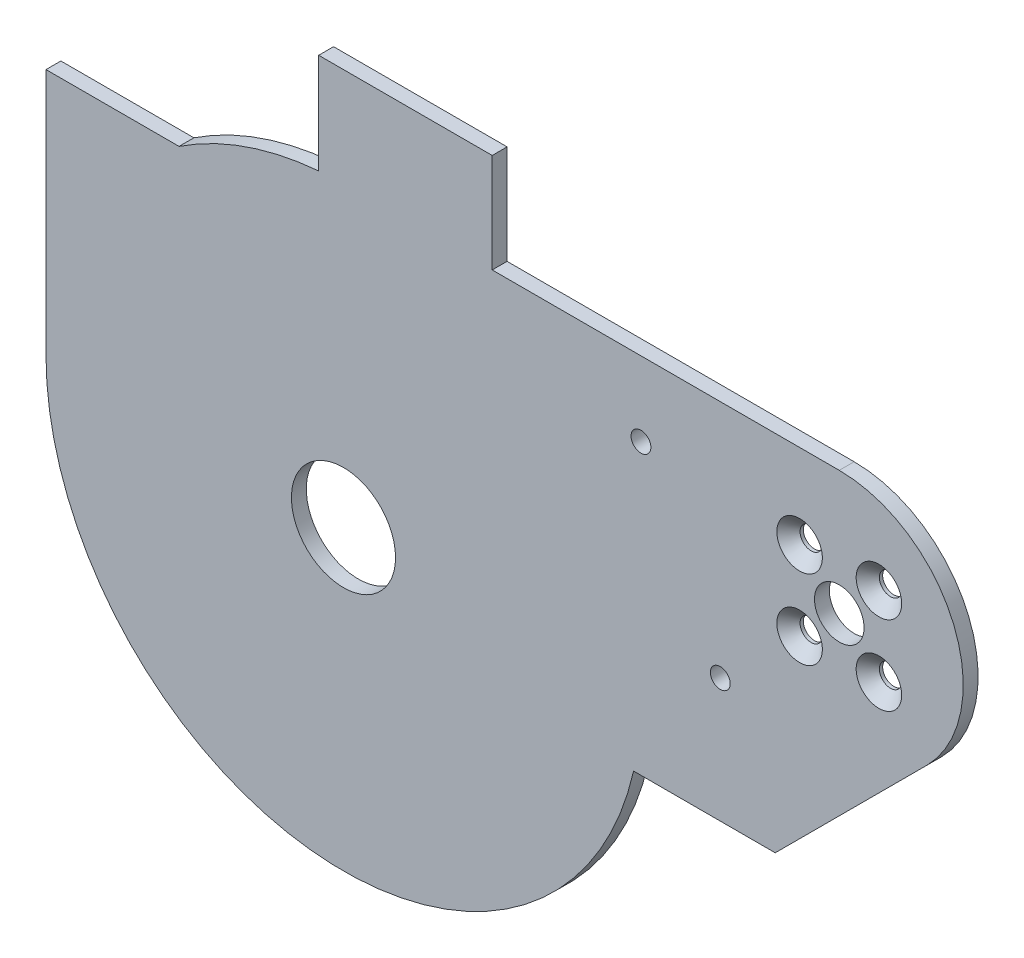
SolidWorks part; units mm, degrees
ref_plane "前视基准面" through (0, 0, 0) normal (0, 0, 1) x (1, 0, 0)
ref_plane "上视基准面" through (0, 0, 0) normal (0, 1, 0) x (1, 0, 0)
ref_plane "右视基准面" through (0, 0, 0) normal (1, 0, 0) x (0, 0, -1)
sketch "Sketch1" plane through (0, 0, 0) normal (0, 0, 1) x (1, 0, 0)
  line L0 (-10.9179, 60) -> (113.3582, 60) construction
  line L3 (-33.1662, 50) -> (-60, 50)
  line L4 (-60, 0) -> (-60, 50)
  line L6 (67.51, -32.8453) -> (81.2655, -19.0899) construction
  line L7 (81.2655, -19.0899) -> (117.6777, 17.3223)
  line L12 (58.5132, -13.2742) -> (87.0811, -13.2742)
  line L13 (0, 60) -> (100, 60)
  arc A0 (0, 60) -> (58.5132, -13.2742) centre (0, 0) ccw
  circle A2 centre (0, 0) radius 10.5
  arc A8 (117.6777, 17.3223) -> (100, 60) centre (100, 35) ccw
  circle A9 centre (100, 35) radius 5
  dimension "D1" = 120
  dimension "D3" = 21
  dimension "D5" = 50
  dimension "D4" = 100
  dimension "D6" = 10
extrude "Boss-Extrude1" add sketch "Sketch1" along normal blind 3
sketch "Sketch2" plane through (0, 0, 3) normal (0, 0, 1) x (1, 0, 0)
  line L1 (-60, 0) -> (-60, 50) construction
  line L2 (0, 60) -> (100, 60) construction
  line L3 (58.5132, -13.2742) -> (87.0811, -13.2742) construction
  circle A1 centre (0, 0) radius 57
  circle A2 centre (60, 45) radius 2
  circle A3 centre (76, 11.7258) radius 2
  circle A6 centre (100, 35) radius 14
  dimension "D1" = 15
  dimension "D4" = 136
  dimension "D5" = 28
  dimension "D2" = 120
  dimension "D3" = 25
extrude "Cut-Extrude1" cut sketch "Sketch2" against normal up to next contours A2 | A3
sketch "Sketch3" plane through (0, 0, 0) normal (0, 0, -1) x (-1, 0, 0)
  line L4 (-30, 0) -> (-30, 80)
  line L5 (-30, 80) -> (5, 80)
  line L6 (5, 80) -> (5, 48)
  line L7 (5, 48) -> (25.3049, 16.1141)
  circle A2 centre (0, 0) radius 10.5
  arc A4 (-30, 0) -> (25.3049, 16.1141) centre (0, 0) ccw
  dimension "D1" = 80
  dimension "D2" = 35
  dimension "D3" = 32
extrude "Boss-Extrude2" add sketch "Sketch3" against normal blind 3
sketch "Sketch4" plane through (0, 0, 0) normal (0, 0, -1) x (-1, 0, 0)
  line L0 (-30, 80) -> (5, 80) construction
  line L1 (5, 80) -> (5, 48) construction
  line L3 (-20, 65.5961) -> (-5, 65.5961)
  line L4 (-20, 65.5961) -> (-20, 63.5961)
  line L5 (-20, 63.5961) -> (-5, 63.5961)
  line L6 (-5, 65.5961) -> (-5, 63.5961)
  line L7 (-20, 65.5961) -> (-5, 63.5961) construction
  line L8 (-20, 63.5961) -> (-5, 65.5961) construction
  line L9 (-13.5, 72.0961) -> (-11.5, 72.0961)
  line L10 (-13.5, 72.0961) -> (-13.5, 57.0961)
  line L11 (-13.5, 57.0961) -> (-11.5, 57.0961)
  line L12 (-11.5, 72.0961) -> (-11.5, 57.0961)
  line L13 (-13.5, 72.0961) -> (-11.5, 57.0961) construction
  line L14 (-13.5, 57.0961) -> (-11.5, 72.0961) construction
  point P5 (-12.5, 64.5961)
  point P10 (-12.5, 80)
  point P11 (-12.5, 64.5961)
  dimension "D1" = 15
  dimension "D2" = 2
  dimension "D3" = 0
  dimension "D4" = 15
  dimension "D5" = 2
extrude "Boss-Extrude3" add sketch "Sketch4" along normal blind 1 contours L12 L9 L10 L3 | L10 L3 L4 L5 | L12 L3 L10 L5 | L3 L12 L5 L6 | L12 L5 L10 L11
sketch "Sketch5" plane through (0, 0, 3) normal (0, 0, 1) x (1, 0, 0)
  line L0 (100, 48.4826) -> (100, 24.1919) construction
  line L1 (89.5844, 35) -> (110.5191, 35) construction
  circle A0 centre (92, 43) radius 2
  circle A1 centre (108, 43) radius 2
  circle A2 centre (108, 27) radius 2
  circle A3 centre (92, 27) radius 2
  dimension "D1" = 8
  dimension "D2" = 8
extrude "Cut-Extrude2" cut sketch "Sketch5" against normal blind 10
hole_wizard "CSK for M4 Hex Socket Countersunk Head Screw1" positions "Sketch7" profile "Sketch8" countersink size "M4" standard "DIN" end condition through all
sketch "Sketch7" plane through (0, 0, 3) normal (0, 0, 1) x (1, 0, 0)
  point P0 (92, 43)
  point P3 (108, 43)
  point P6 (92, 27)
  point P9 (108, 27)
sketch "Sketch8" plane through (92, 43, 3) normal (1, 0, 0) x (0, -1, 0)
  line L0 (0, 0) -> (0, 4)
  line L1 (0, 4) -> (2.25, 4)
  line L2 (2.25, 4) -> (2.25, 2.34)
  line L3 (2.25, 2.34) -> (4.59, 0)
  line L5 (4.59, 0) -> (0, 0)
  line L6 (-2.25, 2.34) -> (-4.59, 0) construction
  line L11 (0, -6.35) -> (0, 107.95) construction
  dimension "Thru Hole Dia." = 4.5
  dimension "Thru Hole Depth" = 4
  dimension "Near C'Sink Dia." = 9.18
  dimension "Near C'Sink Angle" = 90
